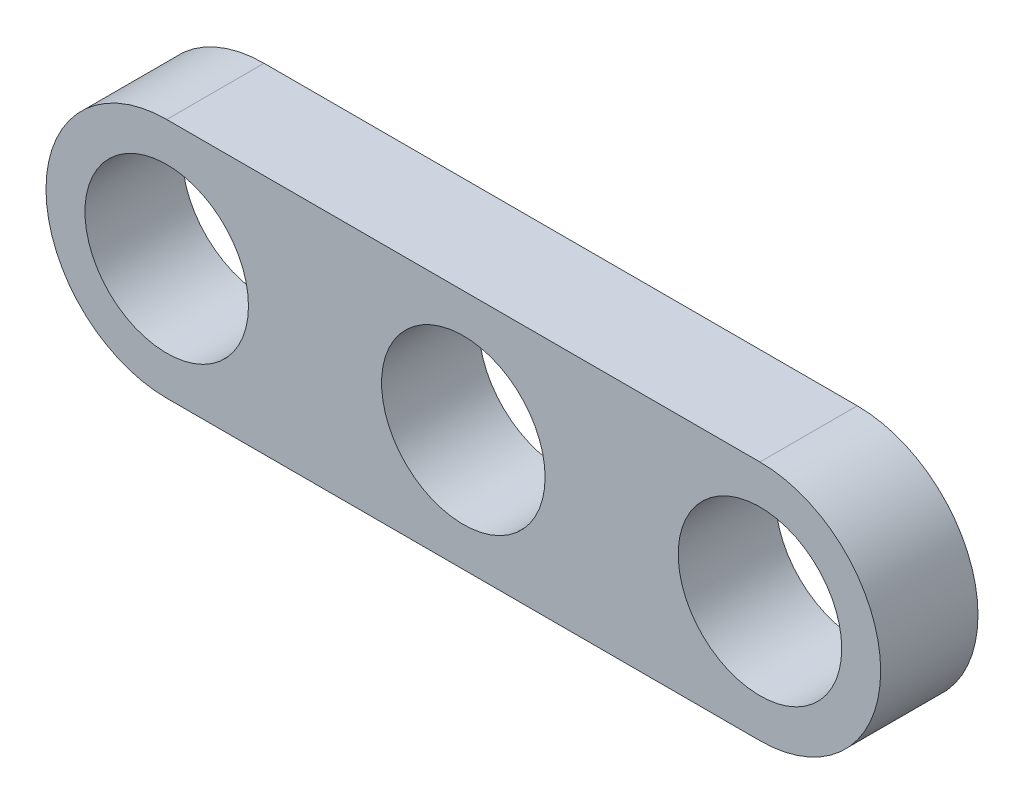
SolidWorks part; units mm, degrees
material "Медь"
ref_plane "Спереди" through (0, 0, 0) normal (0, 0, 1) x (1, 0, 0)
ref_plane "Сверху" through (0, 0, 0) normal (0, 1, 0) x (1, 0, 0)
ref_plane "Справа" through (0, 0, 0) normal (1, 0, 0) x (0, 0, -1)
sketch "Эскиз1" plane through (0, 0, 0) normal (0, 0, 1) x (1, 0, 0)
  line L0 (-15.237, 6.2) -> (15.237, 6.2)
  line L1 (-15.237, -6.2) -> (15.237, -6.2)
  circle A0 centre (-15.237, 0) radius 4.2
  circle A1 centre (0, 0) radius 4.2
  circle A2 centre (15.237, 0) radius 4.2
  arc A3 (15.237, -6.2) -> (15.237, 6.2) centre (15.237, 0) ccw
  arc A4 (-15.237, 6.2) -> (-15.237, -6.2) centre (-15.237, 0) ccw
extrude "Бобышка-Вытянуть1" add sketch "Эскиз1" along normal blind 5
